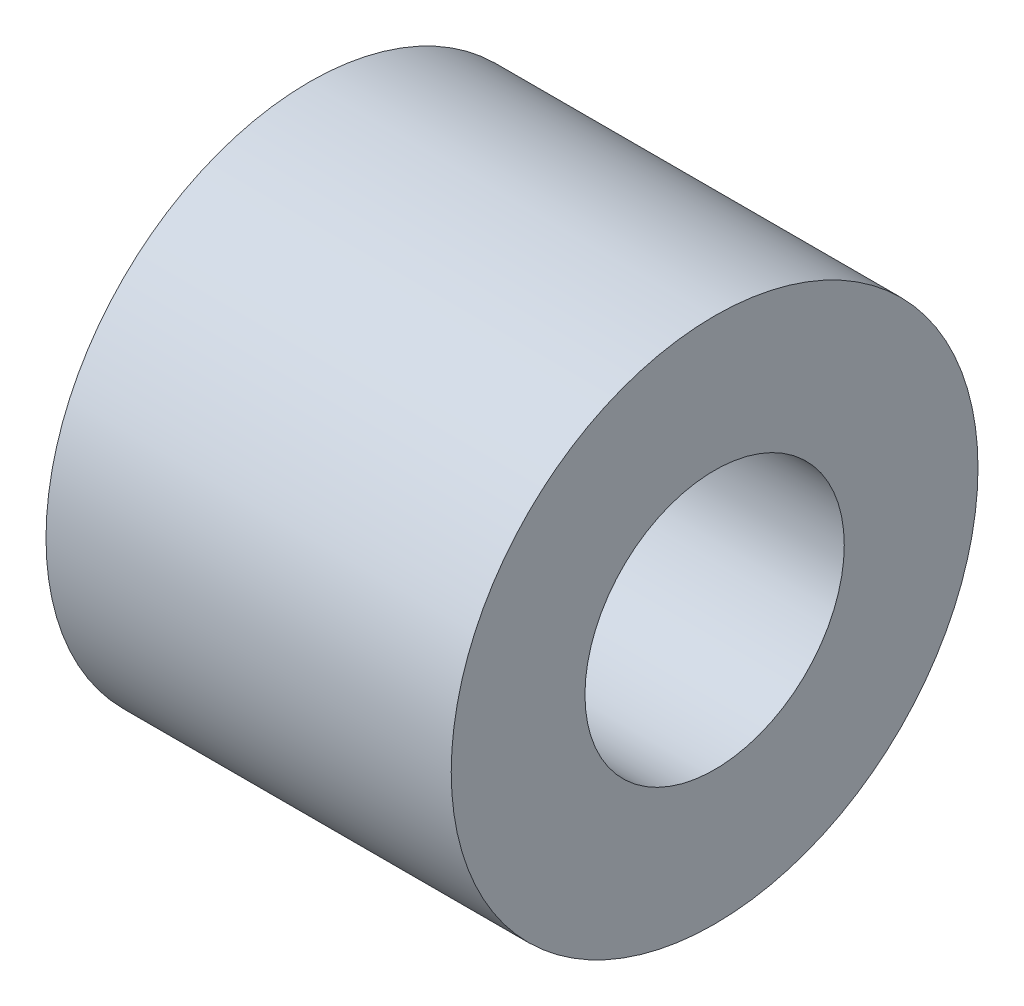
SolidWorks part; units mm, degrees
ref_plane "Front" through (0, 0, 0) normal (0, 0, 1) x (1, 0, 0)
ref_plane "Top" through (0, 0, 0) normal (0, 1, 0) x (1, 0, 0)
ref_plane "Right" through (0, 0, 0) normal (1, 0, 0) x (0, 0, -1)
sketch "Sketch1" plane through (0, 0, 0) normal (1, 0, 0) x (0, 0, -1)
  circle A0 centre (0, 0) radius 3.2
  circle A1 centre (0, 0) radius 6.5
extrude "Boss-Extrude1" add sketch "Sketch1" along normal blind 10
